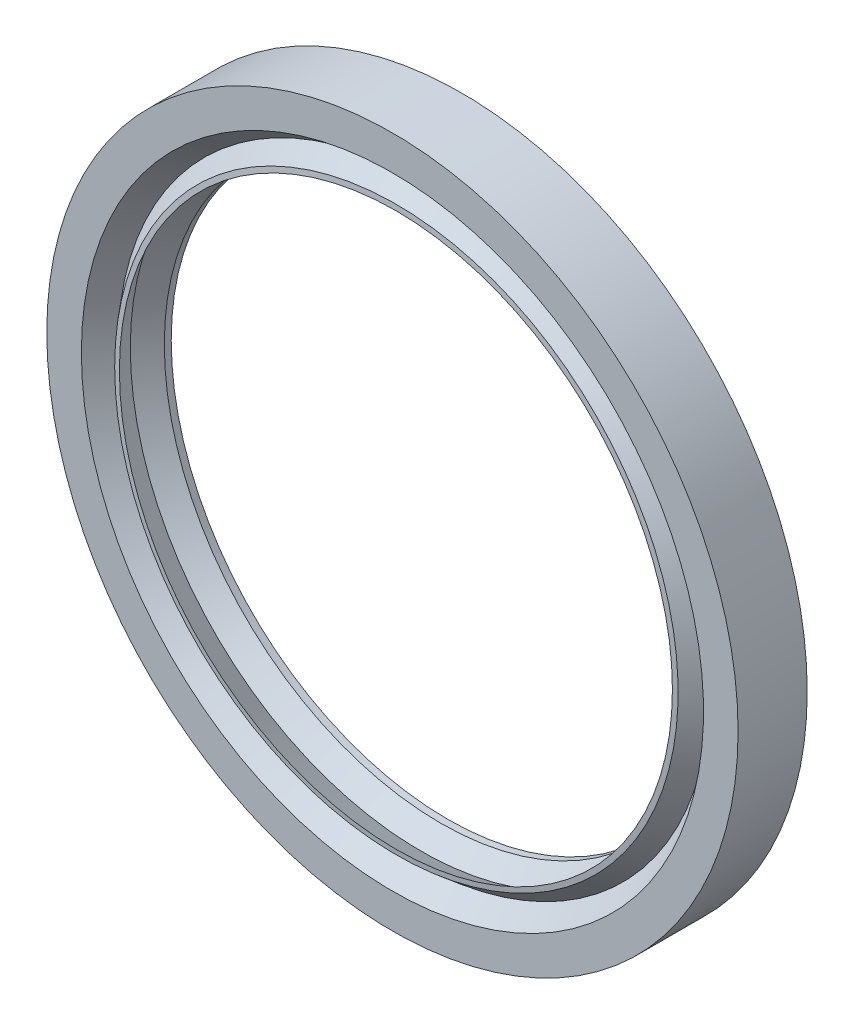
SolidWorks part; units mm, degrees
material "Viton"
ref_plane "Front Plane" through (0, 0, 0) normal (0, 0, 1) x (1, 0, 0)
ref_plane "Top Plane" through (0, 0, 0) normal (0, 1, 0) x (1, 0, 0)
ref_plane "Right Plane" through (0, 0, 0) normal (1, 0, 0) x (0, 0, -1)
sketch "Sketch1" plane through (0, 0, 0) normal (1, 0, 0) x (0, 0, -1)
  line L0 (10, 50) -> (0, 50)
  line L1 (0, 50) -> (0, 45)
  line L2 (0, 45) -> (3.0691, 42.8078)
  line L3 (7, 40) -> (8, 40)
  line L4 (8, 40) -> (2, 46)
  line L5 (2, 46) -> (2, 48)
  line L6 (2, 48) -> (10, 48)
  line L7 (10, 48) -> (10, 50)
  line L8 (0, 0) -> (-17.0366, 0) construction
  line L9 (4.1295, 42.0503) -> (0.5, 40)
  line L10 (0.5, 40) -> (0.573, 40.753)
  line L11 (0.573, 40.753) -> (3.0691, 42.8078)
  line L12 (4.1295, 42.0503) -> (7, 40)
  dimension "D1" = 80
  dimension "D2" = 100
  dimension "D3" = 90
  dimension "D4" = 2
  dimension "D5" = 2
  dimension "D6" = 1
  dimension "D7" = 10
  dimension "D8" = 7
  dimension "D9" = 1
  dimension "D10" = 115
  dimension "D11" = 10
  dimension "D12" = 3.7716
  dimension "D13" = 0.5
  dimension "D14" = 55
revolve "Revolve1" add sketch "Sketch1" angle 360 about L8
other "Freeze***"
